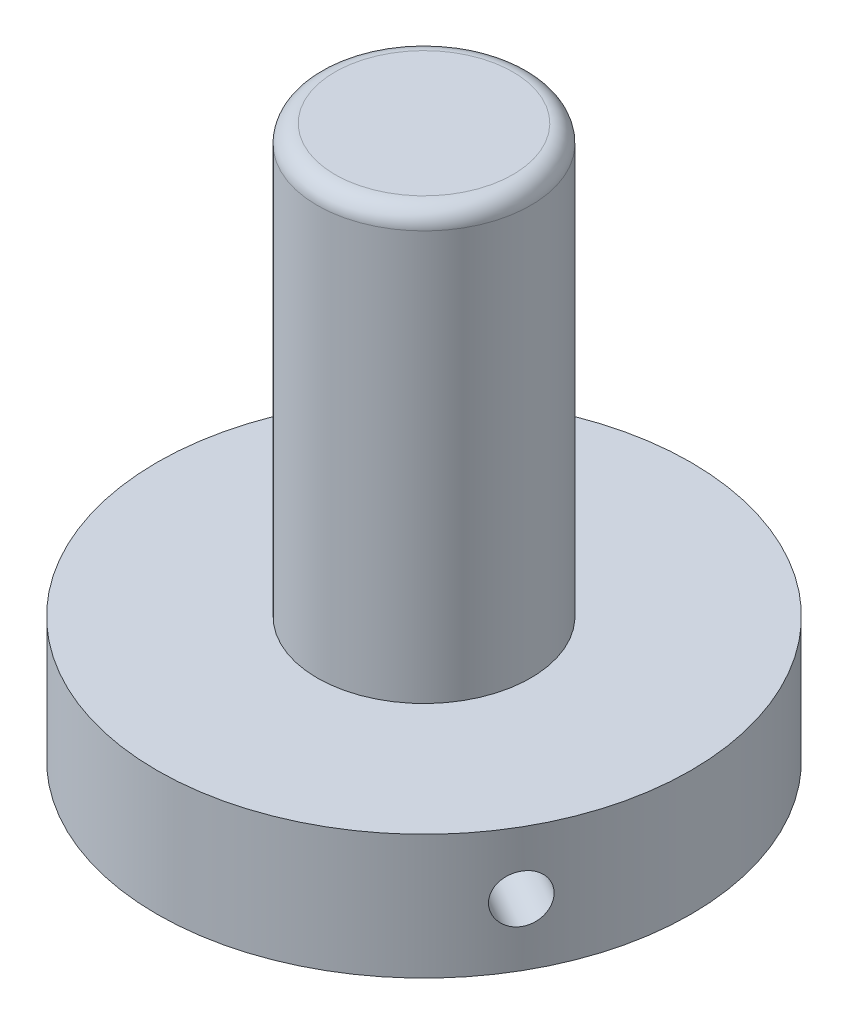
SolidWorks part; units mm, degrees
ref_plane "Přední rovina" through (0, 0, 0) normal (0, 0, 1) x (1, 0, 0)
ref_plane "Horní rovina" through (0, 0, 0) normal (0, 1, 0) x (1, 0, 0)
ref_plane "Pravá rovina" through (0, 0, 0) normal (1, 0, 0) x (0, 0, -1)
sketch "Skica1" plane through (0, 0, 0) normal (0, 1, 0) x (1, 0, 0)
  circle A0 centre (0, 0) radius 15
  dimension "D1" = 30
extrude "Přidat vysunutím1" add sketch "Skica1" along normal blind 7
sketch "Skica3" plane through (0, 7, 0) normal (0, 1, 0) x (1, 0, 0)
  circle A0 centre (0, 0) radius 6
  dimension "D1" = 12
extrude "Přidat vysunutím2" add sketch "Skica3" along normal blind 24
fillet "Zaoblit1" radius 1 1 edges at (0, 31, 6)
sketch "Skica5" plane through (0, 0, 0) normal (0, -1, 0) x (1, 0, 0)
  circle A0 centre (0, 0) radius 2.5
  dimension "D1" = 5
extrude "Odebrat vysunutím1" cut sketch "Skica5" against normal blind 22
fillet "Zaoblit3" radius 0.5 1 edges at (0, 0, -2.5)
sketch "Skica6" plane through (0, 0, 0) normal (0, 0, 1) x (1, 0, 0)
  line L0 (0, 0) -> (0, 7) construction
  line L1 (15, 7) -> (-15, 7) construction
  circle A0 centre (0, 3.5) radius 1.35
  dimension "D1" = 2.7
extrude "Odebrat vysunutím3" cut sketch "Skica6" against normal through all
sketch "Skica7" plane through (0, 0, 0) normal (0, 0, 1) x (1, 0, 0)
  line L0 (0, 0) -> (0, -10.5469) construction
  point P3 (0, 0)
  point P4 (0, -8.6681)
  point P5 (0, -10.5469)
pattern_circular "Kruhové pole1" count 3 every 120 about axis through (0, 0, 0) along (0, -1, 0) of "Odebrat vysunutím3"
